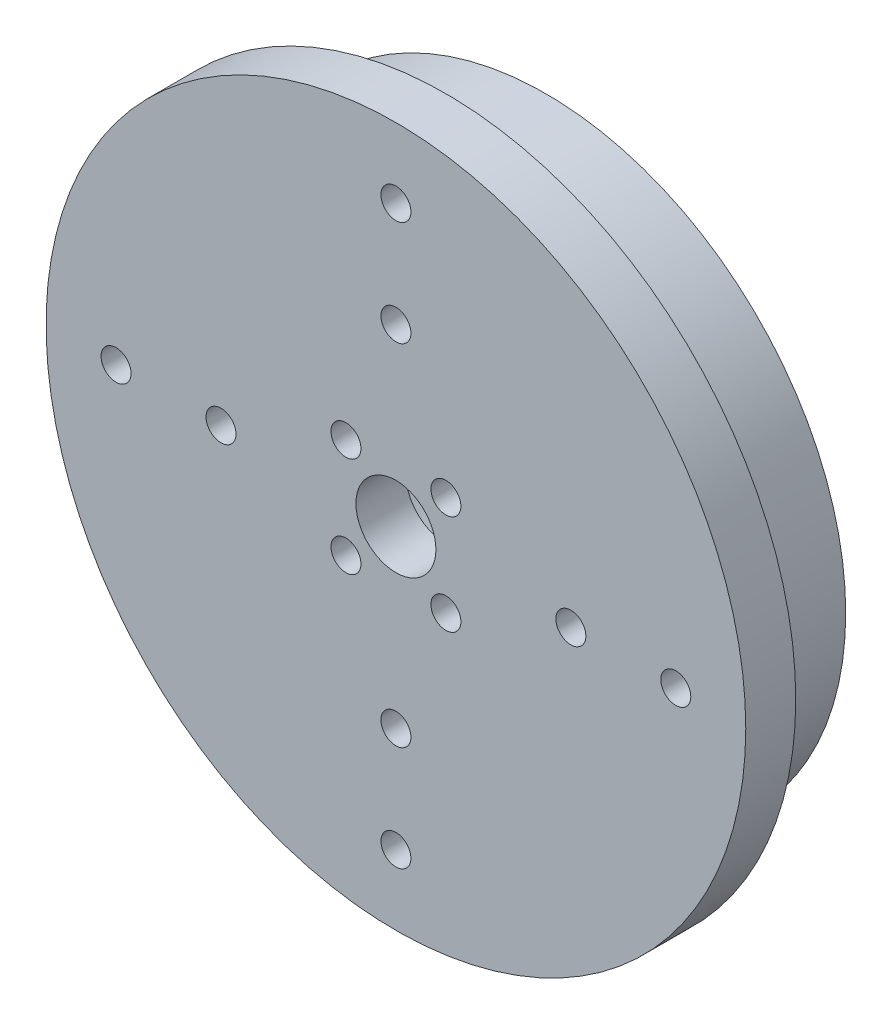
SolidWorks part; units mm, degrees
ref_plane "前视基准面" through (0, 0, 0) normal (0, 0, 1) x (1, 0, 0)
ref_plane "上视基准面" through (0, 0, 0) normal (0, 1, 0) x (1, 0, 0)
ref_plane "右视基准面" through (0, 0, 0) normal (1, 0, 0) x (0, 0, -1)
other "Configuration Table"
sketch "草图1" plane through (0, 0, 0) normal (0, 0, 1) x (1, 0, 0)
  circle A0 centre (0, 0) radius 35
  circle A1 centre (0, 0) radius 26
  circle A2 centre (0, 0) radius 30
  circle A4 centre (0, 28) radius 1.5
  circle A5 centre (28, 0) radius 1.5
  circle A6 centre (0, -28) radius 1.5
  circle A7 centre (-28, 0) radius 1.5
  circle A8 centre (0, 0) radius 20
  circle A9 centre (0, 0) radius 15
  circle A11 centre (0, 17.5) radius 1.5
  circle A12 centre (17.5, 0) radius 1.5
  circle A13 centre (0, -17.5) radius 1.5
  circle A14 centre (-17.5, 0) radius 1.5
  circle A15 centre (0, 0) radius 12.5
  point P17 (0, 0)
  point P29 (0, 0)
  dimension "D1" = 70
  dimension "D2" = 52
  dimension "D3" = 60
  dimension "D4" = 25
  dimension "D5" = 3
  dimension "D7" = 40
  dimension "D8" = 30
  dimension "D10" = 3
  dimension "D6" = 4
  dimension "D11" = 4
extrude "凸台-拉伸1" add sketch "草图1" along normal blind 5 contours A0 A2 | A2 A7 A6 A5 A4 A1 | A1 A8 | A8 A14 A13 A12 A11 A9 | A9 A15 | A15
sketch "草图2" plane through (0, 0, 0) normal (0, 0, -1) x (-1, 0, 0)
  circle A0 centre (0, 0) radius 26
  circle A1 centre (0, 0) radius 30
  circle A2 centre (0, 0) radius 15
  circle A3 centre (0, 0) radius 20
  circle M2 centre (28, 0) radius 1.5
  circle M3 centre (0, -28) radius 1.5
  circle M4 centre (-28, 0) radius 1.5
  circle M5 centre (0, 28) radius 1.5
  circle M6 centre (17.5, 0) radius 1.5
  circle M7 centre (0, -17.5) radius 1.5
  circle M8 centre (-17.5, 0) radius 1.5
  circle M9 centre (0, 17.5) radius 1.5
extrude "凸台-拉伸2" add sketch "草图2" along normal blind 10 contours A1 A0 M3 M5 M4 M2 | A3 A2 M6 M8 M9 M7
sketch "草图3" plane through (0, 0, 0) normal (0, 0, -1) x (-1, 0, 0)
  line L1 (-5, -5) -> (5, -5)
  line L2 (-5, -5) -> (-5, 5)
  line L3 (-5, 5) -> (5, 5)
  line L4 (5, -5) -> (5, 5)
  line L5 (-5, -5) -> (5, 5) construction
  line L6 (-5, 5) -> (5, -5) construction
  circle A0 centre (0, 0) radius 11
  circle A1 centre (0, 0) radius 4
  circle A2 centre (5, 5) radius 1.5
  circle A3 centre (5, -5) radius 1.5
  circle A4 centre (-5, -5) radius 1.5
  circle A5 centre (-5, 5) radius 1.5
  point P18 (0, 0)
  dimension "D1" = 22
  dimension "D2" = 8
  dimension "D5" = 3
  dimension "D3" = 10
  dimension "D4" = 10
  dimension "D6" = 4
extrude "切除-拉伸1" cut sketch "草图3" against normal blind 10 contours L3 A5 L2 | A1 | A4 | A3 | A2
